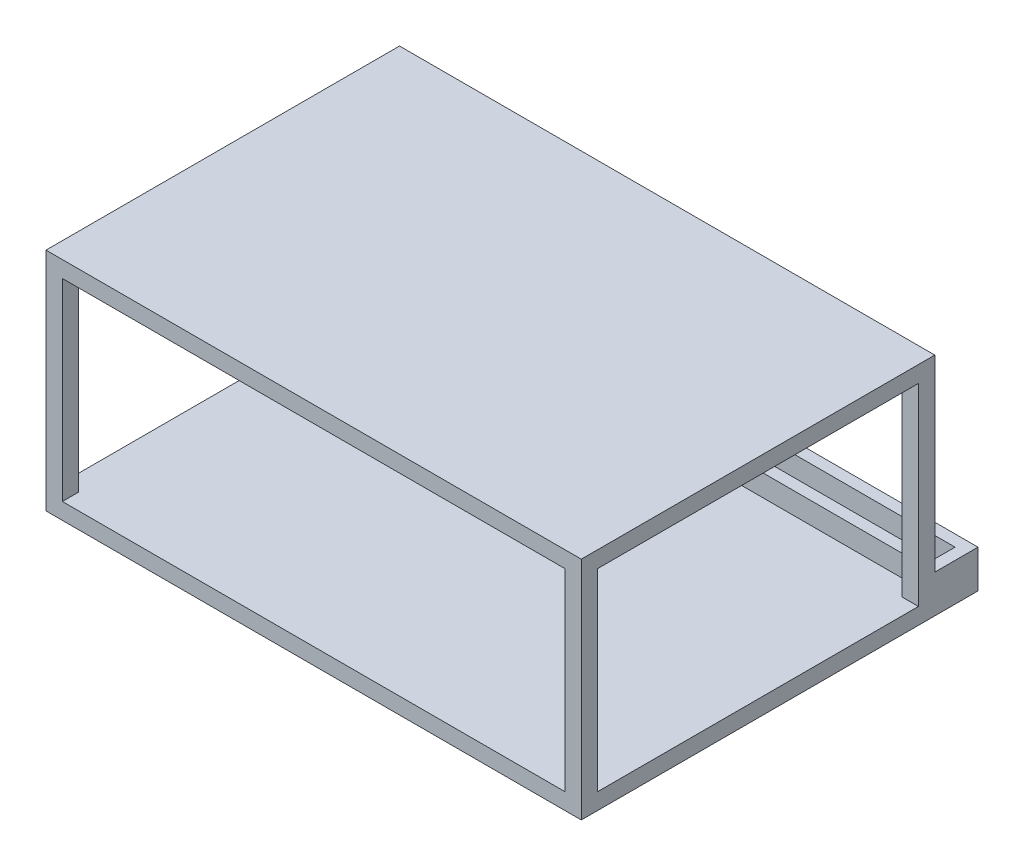
SolidWorks part; units mm, degrees
ref_plane "Front Plane" through (0, 0, 0) normal (0, 0, 1) x (1, 0, 0)
ref_plane "Top Plane" through (0, 0, 0) normal (0, 1, 0) x (1, 0, 0)
ref_plane "Right Plane" through (0, 0, 0) normal (1, 0, 0) x (0, 0, -1)
sketch "Sketch1" plane through (0, 0, 0) normal (0, 1, 0) x (1, 0, 0)
  line L0 (-276.0528, 40.3258) -> (-276.0528, 47.3258) construction
  line L1 (-276.2528, 40.1258) -> (36.8212, 40.1258)
  line L2 (-276.2528, 40.1258) -> (-276.2528, 52.5258)
  line L3 (-276.2528, 52.5258) -> (36.8212, 52.5258)
  line L4 (36.8212, 40.1258) -> (36.8212, 52.5258)
  line L5 (36.6212, 40.3258) -> (36.6212, 47.3258) construction
  line L6 (-269.0528, 52.3258) -> (29.6212, 52.3258) construction
  line L7 (-269.0528, 40.3258) -> (29.6212, 40.3258) construction
  line L8 (-283.2528, 33.1258) -> (-283.2528, 59.5258)
  line L9 (-283.2528, 59.5258) -> (43.8212, 59.5258)
  line L10 (43.8212, 33.1258) -> (43.8212, 59.5258)
  line L11 (-283.2528, 33.1258) -> (43.8212, 33.1258)
  dimension "D1" = 0.2
  dimension "D2" = 0.2
  dimension "D3" = 0.2
  dimension "D4" = 0.2
  dimension "D5" = 7
extrude "Boss-Extrude1" add sketch "Sketch1" along normal blind 20
sketch "Sketch2" plane through (0, 0, 0) normal (0, -1, 0) x (1, 0, 0)
  line L0 (-283.2528, -59.5258) -> (-283.2528, -33.1258) construction
  line L1 (-283.2528, -59.5258) -> (43.8212, -59.5258)
  line L2 (-283.2528, -59.5258) -> (-283.2528, 182.8742)
  line L3 (-283.2528, 182.8742) -> (43.8212, 182.8742)
  line L4 (43.8212, -59.5258) -> (43.8212, 182.8742)
  line L5 (43.8212, -59.5258) -> (-283.2528, -59.5258) construction
  line L6 (43.8212, -33.1258) -> (43.8212, -59.5258) construction
  line L7 (-276.0528, 64.6742) -> (-283.2528, 64.6742) construction
  line L8 (-276.0528, -39.3258) -> (-276.0528, 168.6742) construction
  line L9 (-119.7158, 175.6742) -> (-119.7158, 182.8742) construction
  line L10 (-269.0528, 175.6742) -> (29.6212, 175.6742) construction
extrude "Boss-Extrude2" add sketch "Sketch2" along normal blind 3.175
sketch "Sketch3" plane through (0, 0, 0) normal (0, 1, 0) x (1, 0, 0)
  line L4 (43.8212, 33.1258) -> (-283.2528, 33.1258)
  line L5 (-283.2528, 33.1258) -> (-283.2528, -182.8742)
  line L6 (-283.2528, -182.8742) -> (43.8212, -182.8742)
  line L7 (43.8212, -182.8742) -> (43.8212, 33.1258)
  line L8 (43.8212, 33.1258) -> (-283.2528, 33.1258)
  line L9 (-283.2528, 33.1258) -> (-283.2528, -182.8742)
  line L10 (-283.2528, -182.8742) -> (43.8212, -182.8742)
  line L11 (43.8212, -182.8742) -> (43.8212, 33.1258)
  dimension "D1" = 0
extrude "Boss-Extrude3" add sketch "Sketch3" along normal blind 134.85
sketch "Sketch4" plane through (-283.2528, 0, 0) normal (-1, 0, 0) x (0, 0, 1)
  line L6 (-23.1258, 10) -> (-23.1258, 6.825)
  line L12 (-49.5258, 10) -> (-49.5258, 6.825)
  line L13 (-49.5258, 6.825) -> (172.8742, 6.825)
  line L14 (172.8742, 6.825) -> (172.8742, 124.85)
  line L15 (172.8742, 124.85) -> (-23.1258, 124.85)
  line L16 (-23.1258, 124.85) -> (-23.1258, 10)
  line L17 (-23.1258, 10) -> (-49.5258, 10)
  line L18 (-49.5258, 10) -> (-49.5258, 6.825) construction
  line L19 (-23.1258, 6.825) -> (172.8742, 6.825)
  line L20 (172.8742, 6.825) -> (172.8742, 124.85)
  line L21 (172.8742, 124.85) -> (-23.1258, 124.85)
  line L22 (-23.1258, 124.85) -> (-23.1258, 10)
  line L23 (-23.1258, 10) -> (-49.5258, 10) construction
  dimension "D1" = 10
extrude "Cut-Extrude1" cut sketch "Sketch4" against normal up to next
sketch "Sketch5" plane through (0, 0, 182.8742) normal (0, 0, 1) x (1, 0, 0)
  line L8 (33.8212, 6.825) -> (33.8212, 124.85)
  line L9 (33.8212, 124.85) -> (-273.2528, 124.85)
  line L10 (-273.2528, 124.85) -> (-273.2528, 6.825)
  line L11 (-273.2528, 6.825) -> (33.8212, 6.825)
  line L12 (33.8212, 6.825) -> (33.8212, 124.85)
  line L13 (33.8212, 124.85) -> (-273.2528, 124.85)
  line L14 (-273.2528, 124.85) -> (-273.2528, 6.825)
  line L15 (-273.2528, 6.825) -> (33.8212, 6.825)
  dimension "D1" = 10
extrude "Cut-Extrude2" cut sketch "Sketch5" against normal up to surface (216 mm away) up to face at (-119.7158, 77.425, -33.1258)
equation "\"TOLERANCE\"= .2"
